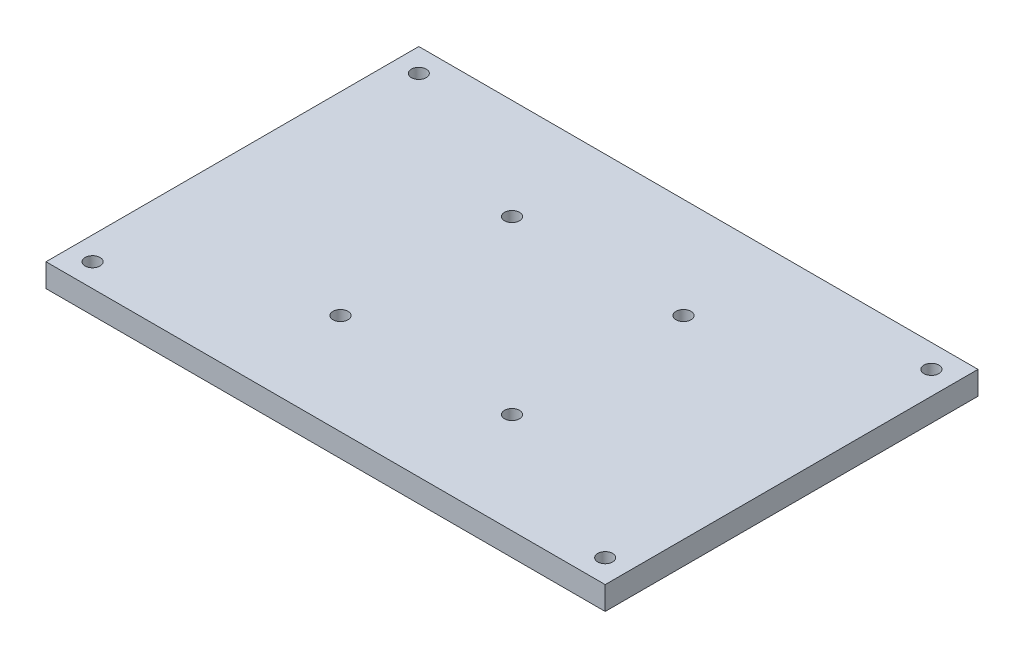
SolidWorks part; units mm, degrees
ref_plane "Plan de face" through (0, 0, 0) normal (0, 0, 1) x (1, 0, 0)
ref_plane "Plan de dessus" through (0, 0, 0) normal (0, 1, 0) x (1, 0, 0)
ref_plane "Plan de droite" through (0, 0, 0) normal (1, 0, 0) x (0, 0, -1)
sketch "Esquisse1" plane through (0, 0, 0) normal (0, 1, 0) x (1, 0, 0)
  line L1 (0, 0) -> (120, 0)
  line L2 (0, 0) -> (0, 80)
  line L3 (0, 80) -> (120, 80)
  line L4 (120, 0) -> (120, 80)
  dimension "D1" = 120
  dimension "D2" = 80
extrude "Boss.-Extru.1" add sketch "Esquisse1" along normal blind 5
sketch "Esquisse2" plane through (0, 5, 0) normal (0, 1, 0) x (1, 0, 0)
  line L2 (0, 40) -> (120, 40) construction
  line L3 (0, 80) -> (0, 0) construction
  line L4 (120, 0) -> (120, 80) construction
  line L5 (60, 80) -> (60, 0) construction
  line L6 (120, 80) -> (0, 80) construction
  line L7 (0, 0) -> (120, 0) construction
  circle A4 centre (5, 75) radius 1.6
  circle A5 centre (115, 75) radius 1.6
  circle A6 centre (115, 5) radius 1.6
  circle A7 centre (5, 5) radius 1.6
  circle A8 centre (41.6, 58.4) radius 1.6
  circle A9 centre (41.6, 21.6) radius 1.6
  circle A10 centre (78.4, 21.6) radius 1.6
  circle A11 centre (78.4, 58.4) radius 1.6
  dimension "D1" = 3.2
  dimension "D6" = 3.2
  dimension "D2" = 36.8
  dimension "D3" = 36.8
  dimension "D7" = 5
  dimension "D8" = 5
extrude "Enlèv. mat.-Extru.1" cut sketch "Esquisse2" against normal through all
